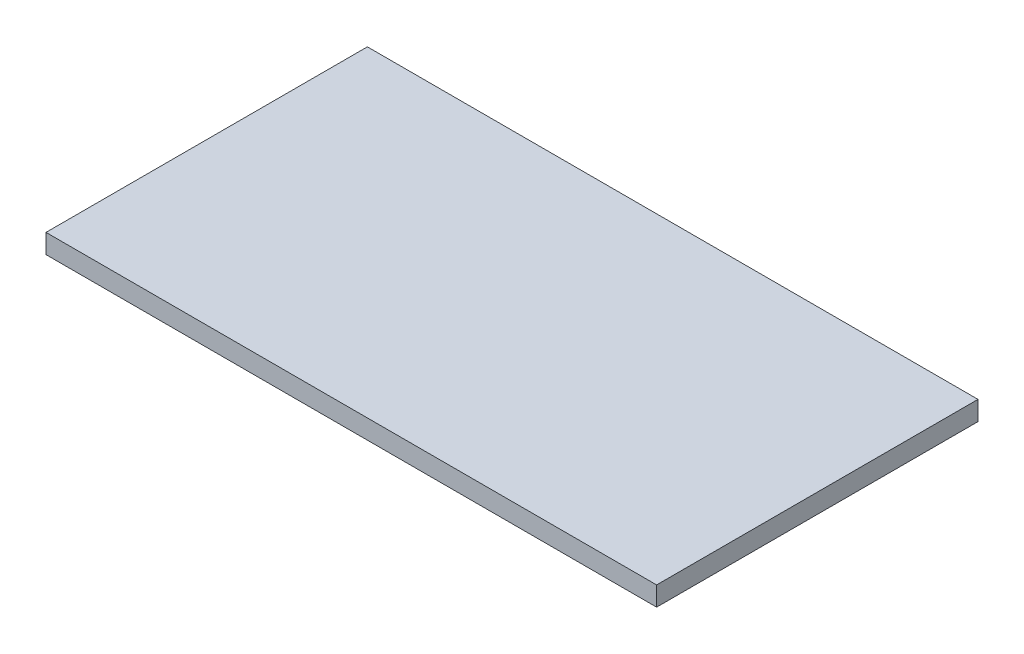
SolidWorks part; units mm, degrees
ref_plane "Plano frontal" through (0, 0, 0) normal (0, 0, 1) x (1, 0, 0)
ref_plane "Plano superior" through (0, 0, 0) normal (0, 1, 0) x (1, 0, 0)
ref_plane "Plano direito" through (0, 0, 0) normal (1, 0, 0) x (0, 0, -1)
sketch "Esboço2" plane through (0, 0, 0) normal (0, 1, 0) x (1, 0, 0)
  line L0 (0, 0) -> (120, 0)
  line L1 (0, 0) -> (0, 100)
  line L2 (120, 0) -> (120, 100)
  line L3 (0, 100) -> (120, 100)
  dimension "D1" = 100
  dimension "D2" = 120
extrude "Ressalto-extrusão1" add sketch "Esboço2" along normal blind 6
sketch "Esboço3" plane through (0, 0, 0) normal (-1, 0, 0) x (0, 0, 1)
  line L1 (-100, 6) -> (0, 6)
  line L2 (-100, 6) -> (-100, 0)
  line L3 (-100, 0) -> (0, 0)
  line L4 (0, 6) -> (0, 0)
extrude "Ressalto-extrusão3" add sketch "Esboço3" along normal blind 70
sketch "Esboço4" plane through (120, 0, 0) normal (1, 0, 0) x (0, 0, -1)
  line L1 (0, 6) -> (100, 6)
  line L2 (0, 6) -> (0, 0)
  line L3 (0, 0) -> (100, 0)
  line L4 (100, 6) -> (100, 0)
